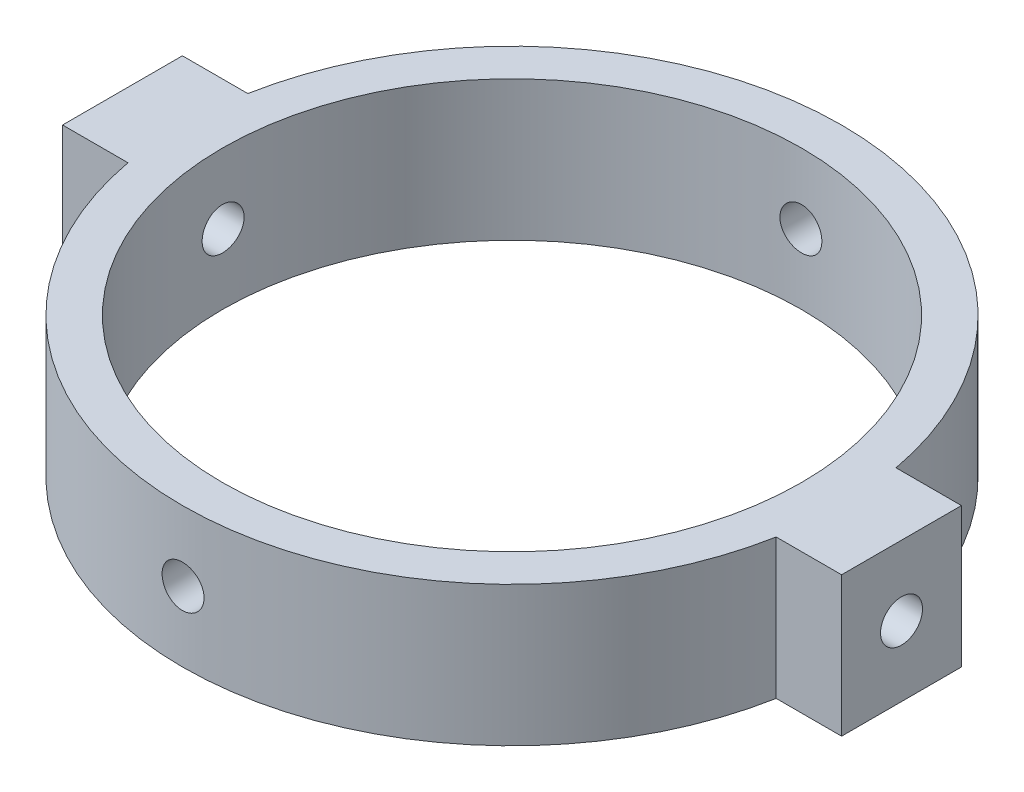
SolidWorks part; units mm, degrees
ref_plane "Front Plane" through (0, 0, 0) normal (0, 0, 1) x (1, 0, 0)
ref_plane "Top Plane" through (0, 0, 0) normal (0, 1, 0) x (1, 0, 0)
ref_plane "Right Plane" through (0, 0, 0) normal (1, 0, 0) x (0, 0, -1)
sketch "Sketch1" plane through (0, 0, 0) normal (0, 1, 0) x (1, 0, 0)
  circle A0 centre (0, 0) radius 29
  circle A1 centre (0, 0) radius 33
  dimension "D1" = 58
  dimension "D2" = 66
extrude "Boss-Extrude1" add sketch "Sketch1" along normal mid plane 14
sketch "Sketch2" plane through (0, 0, 0) normal (0, 1, 0) x (1, 0, 0)
  line L9 (29, -6) -> (39, -6)
  line L10 (29, -6) -> (29, 6)
  line L11 (29, 6) -> (39, 6)
  line L12 (39, -6) -> (39, 6)
  line L13 (29, -6) -> (39, 6) construction
  line L14 (29, 6) -> (39, -6) construction
  line L15 (-29, -6) -> (-39, -6)
  line L16 (-29, -6) -> (-29, 6)
  line L17 (-29, 6) -> (-39, 6)
  line L18 (-39, -6) -> (-39, 6)
  line L19 (-29, -6) -> (-39, 6) construction
  line L20 (-29, 6) -> (-39, -6) construction
  circle A1 centre (0, 0) radius 29 construction
  point P0 (34, 0)
  point P7 (0, 0)
  point P8 (-34, 0)
  dimension "D1" = 12
  dimension "D2" = 10
  dimension "D3" = 10
  dimension "D4" = 12
extrude "Boss-Extrude2" add sketch "Sketch2" along normal mid plane 14
sketch "Sketch5" plane through (-39, 0, 0) normal (-1, 0, 0) x (0, 0, 1)
  circle A0 centre (0, 0) radius 2.1
  dimension "D1" = 4.2
extrude "Cut-Extrude1" cut sketch "Sketch5" against normal through all
sketch "Sketch7" plane through (0, 0, 0) normal (0, 0, 1) x (1, 0, 0)
  circle A0 centre (0, 0) radius 2.1
  dimension "D1" = 4.2
extrude "Cut-Extrude4" cut sketch "Sketch7" against normal through all and the other way through all contours A0
